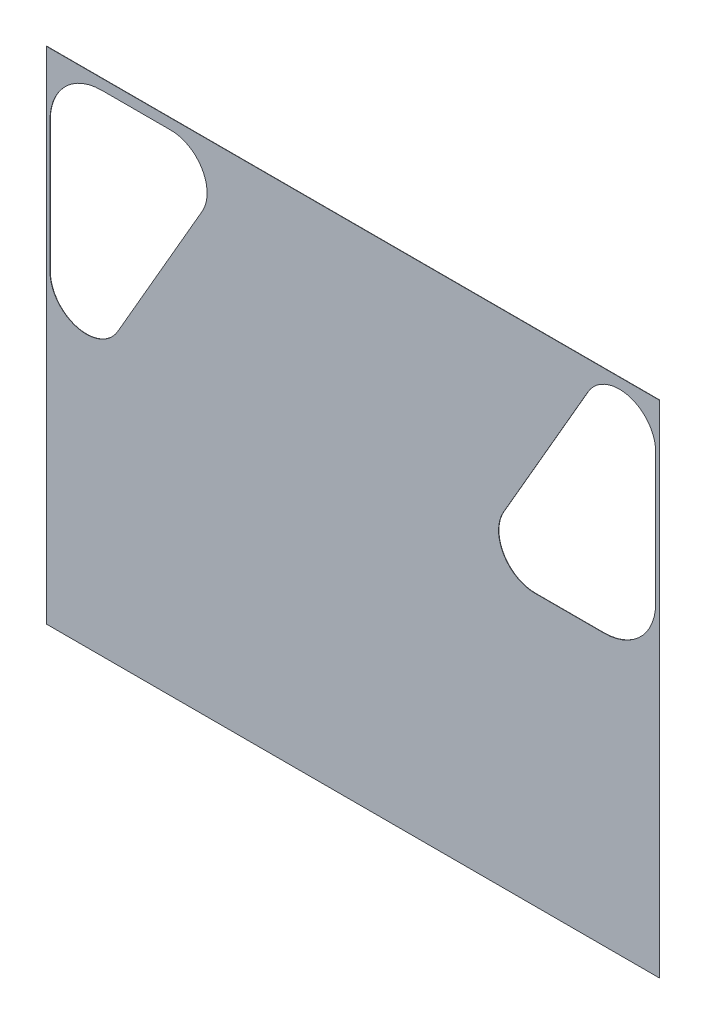
SolidWorks part; units mm, degrees
ref_plane "Front Plane" through (0, 0, 0) normal (0, 0, 1) x (1, 0, 0)
ref_plane "Top Plane" through (0, 0, 0) normal (0, 1, 0) x (1, 0, 0)
ref_plane "Right Plane" through (0, 0, 0) normal (1, 0, 0) x (0, 0, -1)
sketch "Sketch1" plane through (0, 0, 0) normal (0, 0, 1) x (1, 0, 0)
  line L1 (0, 0) -> (1991, 0)
  line L2 (0, 0) -> (0, 1625)
  line L3 (0, 1625) -> (1991, 1625)
  line L4 (1991, 0) -> (1991, 1625)
  dimension "D1" = 1991
  dimension "D2" = 1625
extrude "Boss-Extrude1" add sketch "Sketch1" along normal blind 1
extrude "Cut-Extrude1" cut sketch "Sketch2" against normal through all
sketch "Sketch2" plane through (259.9635, -561.6168, 1) normal (0, 0, 1) x (1, 0, 0)
  line L0 (1498.8454, 2093.6165) -> (1224.6054, 1618.6165)
  line L1 (1326.7965, 1441.6168) -> (1551.0365, 1441.6168)
  line L2 (1719.0365, 1609.6168) -> (1719.0365, 2034.6168)
  line L5 (-247.9635, 1984.6168) -> (-247.9635, 1559.6168)
  line L6 (-27.7724, 1500.617) -> (246.4676, 1975.617)
  line L7 (144.2765, 2152.6168) -> (-79.9635, 2152.6168)
  arc A0 (1551.0365, 1441.6168) -> (1719.0365, 1609.6168) centre (1551.0365, 1609.6168) ccw
  arc A1 (1498.8454, 2093.6165) -> (1719.0365, 2034.6168) centre (1601.0365, 2034.6168) cw
  arc A2 (1224.6054, 1618.6165) -> (1326.7965, 1441.6168) centre (1326.7965, 1559.6168) ccw
  arc A3 (-247.9635, 1559.6168) -> (-27.7724, 1500.617) centre (-129.9635, 1559.6168) ccw
  arc A4 (246.4676, 1975.617) -> (144.2765, 2152.6168) centre (144.2765, 2034.6168) ccw
  arc A5 (-247.9635, 1984.6168) -> (-79.9635, 2152.6168) centre (-79.9635, 1984.6168) cw
  point P22 (54.1362, 1500.617)
